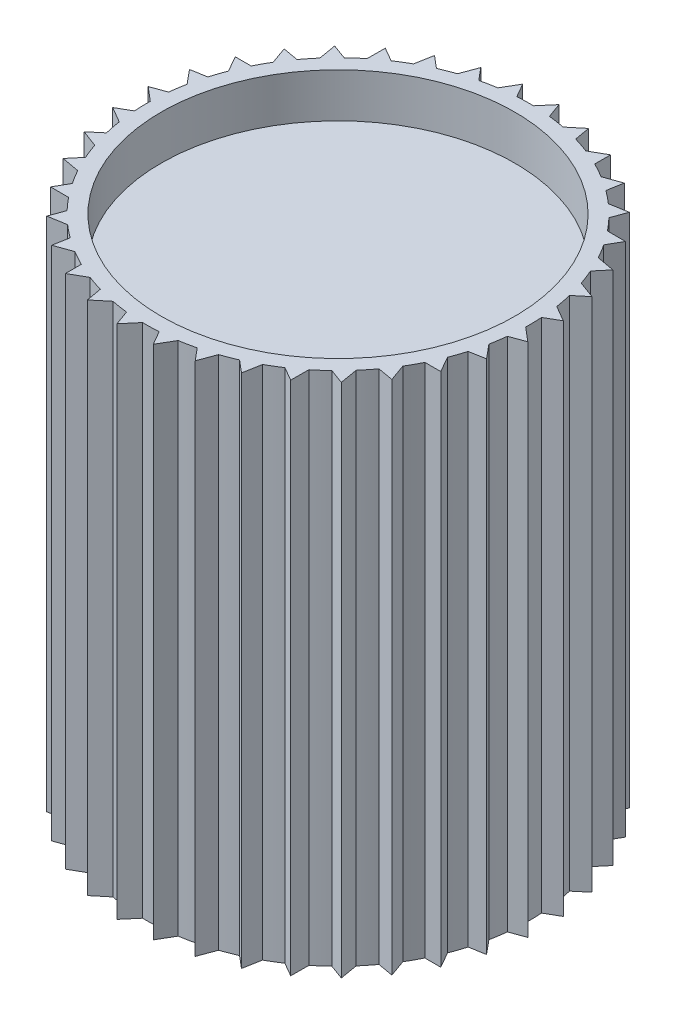
SolidWorks part; units mm, degrees
ref_plane "Front Plane" through (0, 0, 0) normal (0, 0, 1) x (1, 0, 0)
ref_plane "Top Plane" through (0, 0, 0) normal (0, 1, 0) x (1, 0, 0)
ref_plane "Right Plane" through (0, 0, 0) normal (1, 0, 0) x (0, 0, -1)
other "Configuration Table"
sketch "草图1" plane through (0, 0, 0) normal (0, 1, 0) x (1, 0, 0)
  circle A0 centre (0, 0) radius 13
  dimension "D1" = 26
extrude "凸台-拉伸1" add sketch "草图1" along normal blind 35
sketch "草图2" plane through (0, 35, 0) normal (0, 1, 0) x (1, 0, 0)
  circle A0 centre (0, 0) radius 12
  dimension "D1" = 24
extrude "切除-拉伸1" cut sketch "草图2" against normal blind 3
sketch "草图3" plane through (0, 35, 0) normal (0, 1, 0) x (1, 0, 0)
  line L0 (-12.1237, 4.6922) -> (-11.0446, 4.6922)
  line L1 (-12.1237, 4.6922) -> (-12.7329, 5.7609)
  line L2 (-11.0446, 4.6922) -> (-11.6538, 5.7609)
  line L3 (-12.7329, 5.7609) -> (-11.6538, 5.7609)
  line L4 (-11.1247, 6.7262) -> (-10.062, 6.5388)
  line L5 (-11.1247, 6.7262) -> (-11.5391, 7.8844)
  line L6 (-11.5391, 7.8844) -> (-10.4764, 7.6971)
  line L7 (-10.062, 6.5388) -> (-10.4764, 7.6971)
  line L8 (-9.7877, 8.5558) -> (-8.7737, 8.1867)
  line L9 (-9.7877, 8.5558) -> (-9.9947, 9.7684)
  line L10 (-9.9947, 9.7684) -> (-8.9807, 9.3993)
  line L11 (-8.7737, 8.1867) -> (-8.9807, 9.3993)
  line L12 (-8.1533, 10.1254) -> (-7.2188, 9.5859)
  line L13 (-8.1533, 10.1254) -> (-8.1465, 11.3556)
  line L14 (-8.1465, 11.3556) -> (-7.2121, 10.816)
  line L15 (-7.2188, 9.5859) -> (-7.2121, 10.816)
  line L16 (-6.2712, 11.3874) -> (-5.4446, 10.6938)
  line L17 (-6.2712, 11.3874) -> (-6.0509, 12.5977)
  line L18 (-6.0509, 12.5977) -> (-5.2243, 11.9041)
  line L19 (-5.4446, 10.6938) -> (-5.2243, 11.9041)
  line L20 (-4.1985, 12.3034) -> (-3.5049, 11.4767)
  line L21 (-4.1985, 12.3034) -> (-3.7714, 13.457)
  line L22 (-3.7714, 13.457) -> (-3.0778, 12.6304)
  line L23 (-3.5049, 11.4767) -> (-3.0778, 12.6304)
  line L24 (-1.9983, 12.8455) -> (-1.4587, 11.911)
  line L25 (-1.9983, 12.8455) -> (-1.3773, 13.9075)
  line L26 (-1.3773, 13.9075) -> (-0.8378, 12.973)
  line L27 (-1.4587, 11.911) -> (-0.8378, 12.973)
  line L28 (0.2627, 12.9973) -> (0.6317, 11.9834)
  line L29 (0.2627, 12.9973) -> (1.0586, 13.9354)
  line L30 (1.0586, 13.9354) -> (1.4277, 12.9214)
  line L31 (0.6317, 11.9834) -> (1.4277, 12.9214)
  line L32 (2.5157, 12.7543) -> (2.703, 11.6916)
  line L33 (2.5157, 12.7543) -> (3.4624, 13.5398)
  line L34 (3.4624, 13.5398) -> (3.6497, 12.4772)
  line L35 (2.703, 11.6916) -> (3.6497, 12.4772)
  line L36 (4.6922, 12.1237) -> (4.6922, 11.0446)
  line L37 (4.6922, 12.1237) -> (5.7609, 12.7329)
  line L38 (5.7609, 12.7329) -> (5.7609, 11.6538)
  line L39 (4.6922, 11.0446) -> (5.7609, 11.6538)
  line L40 (6.7262, 11.1247) -> (6.5388, 10.062)
  line L41 (6.7262, 11.1247) -> (7.8844, 11.5391)
  line L42 (7.8844, 11.5391) -> (7.6971, 10.4764)
  line L43 (6.5388, 10.062) -> (7.6971, 10.4764)
  line L44 (8.5558, 9.7877) -> (8.1867, 8.7737)
  line L45 (8.5558, 9.7877) -> (9.7684, 9.9947)
  line L46 (9.7684, 9.9947) -> (9.3993, 8.9807)
  line L47 (8.1867, 8.7737) -> (9.3993, 8.9807)
  line L48 (10.1254, 8.1533) -> (9.5859, 7.2188)
  line L49 (10.1254, 8.1533) -> (11.3556, 8.1465)
  line L50 (11.3556, 8.1465) -> (10.816, 7.2121)
  line L51 (9.5859, 7.2188) -> (10.816, 7.2121)
  line L52 (11.3874, 6.2712) -> (10.6938, 5.4446)
  line L53 (11.3874, 6.2712) -> (12.5977, 6.0509)
  line L54 (12.5977, 6.0509) -> (11.9041, 5.2243)
  line L55 (10.6938, 5.4446) -> (11.9041, 5.2243)
  line L56 (12.3034, 4.1985) -> (11.4767, 3.5049)
  line L57 (12.3034, 4.1985) -> (13.457, 3.7714)
  line L58 (13.457, 3.7714) -> (12.6304, 3.0778)
  line L59 (11.4767, 3.5049) -> (12.6304, 3.0778)
  line L60 (12.8455, 1.9983) -> (11.911, 1.4587)
  line L61 (12.8455, 1.9983) -> (13.9075, 1.3773)
  line L62 (13.9075, 1.3773) -> (12.973, 0.8378)
  line L63 (11.911, 1.4587) -> (12.973, 0.8378)
  line L64 (12.9973, -0.2627) -> (11.9834, -0.6317)
  line L65 (12.9973, -0.2627) -> (13.9354, -1.0586)
  line L66 (13.9354, -1.0586) -> (12.9214, -1.4277)
  line L67 (11.9834, -0.6317) -> (12.9214, -1.4277)
  line L68 (12.7543, -2.5157) -> (11.6916, -2.703)
  line L69 (12.7543, -2.5157) -> (13.5398, -3.4624)
  line L70 (13.5398, -3.4624) -> (12.4772, -3.6497)
  line L71 (11.6916, -2.703) -> (12.4772, -3.6497)
  line L72 (12.1237, -4.6922) -> (11.0446, -4.6922)
  line L73 (12.1237, -4.6922) -> (12.7329, -5.7609)
  line L74 (12.7329, -5.7609) -> (11.6538, -5.7609)
  line L75 (11.0446, -4.6922) -> (11.6538, -5.7609)
  line L76 (11.1247, -6.7262) -> (10.062, -6.5388)
  line L77 (11.1247, -6.7262) -> (11.5391, -7.8844)
  line L78 (11.5391, -7.8844) -> (10.4764, -7.6971)
  line L79 (10.062, -6.5388) -> (10.4764, -7.6971)
  line L80 (9.7877, -8.5558) -> (8.7737, -8.1867)
  line L81 (9.7877, -8.5558) -> (9.9947, -9.7684)
  line L82 (9.9947, -9.7684) -> (8.9807, -9.3993)
  line L83 (8.7737, -8.1867) -> (8.9807, -9.3993)
  line L84 (8.1533, -10.1254) -> (7.2188, -9.5859)
  line L85 (8.1533, -10.1254) -> (8.1465, -11.3556)
  line L86 (8.1465, -11.3556) -> (7.2121, -10.816)
  line L87 (7.2188, -9.5859) -> (7.2121, -10.816)
  line L88 (6.2712, -11.3874) -> (5.4446, -10.6938)
  line L89 (6.2712, -11.3874) -> (6.0509, -12.5977)
  line L90 (6.0509, -12.5977) -> (5.2243, -11.9041)
  line L91 (5.4446, -10.6938) -> (5.2243, -11.9041)
  line L92 (4.1985, -12.3034) -> (3.5049, -11.4767)
  line L93 (4.1985, -12.3034) -> (3.7714, -13.457)
  line L94 (3.7714, -13.457) -> (3.0778, -12.6304)
  line L95 (3.5049, -11.4767) -> (3.0778, -12.6304)
  line L96 (1.9983, -12.8455) -> (1.4587, -11.911)
  line L97 (1.9983, -12.8455) -> (1.3773, -13.9075)
  line L98 (1.3773, -13.9075) -> (0.8378, -12.973)
  line L99 (1.4587, -11.911) -> (0.8378, -12.973)
  line L100 (-0.2627, -12.9973) -> (-0.6317, -11.9834)
  line L101 (-0.2627, -12.9973) -> (-1.0586, -13.9354)
  line L102 (-1.0586, -13.9354) -> (-1.4277, -12.9214)
  line L103 (-0.6317, -11.9834) -> (-1.4277, -12.9214)
  line L104 (-2.5157, -12.7543) -> (-2.703, -11.6916)
  line L105 (-2.5157, -12.7543) -> (-3.4624, -13.5398)
  line L106 (-3.4624, -13.5398) -> (-3.6497, -12.4772)
  line L107 (-2.703, -11.6916) -> (-3.6497, -12.4772)
  line L108 (-4.6922, -12.1237) -> (-4.6922, -11.0446)
  line L109 (-4.6922, -12.1237) -> (-5.7609, -12.7329)
  line L110 (-5.7609, -12.7329) -> (-5.7609, -11.6538)
  line L111 (-4.6922, -11.0446) -> (-5.7609, -11.6538)
  line L112 (-6.7262, -11.1247) -> (-6.5388, -10.062)
  line L113 (-6.7262, -11.1247) -> (-7.8844, -11.5391)
  line L114 (-7.8844, -11.5391) -> (-7.6971, -10.4764)
  line L115 (-6.5388, -10.062) -> (-7.6971, -10.4764)
  line L116 (-8.5558, -9.7877) -> (-8.1867, -8.7737)
  line L117 (-8.5558, -9.7877) -> (-9.7684, -9.9947)
  line L118 (-9.7684, -9.9947) -> (-9.3993, -8.9807)
  line L119 (-8.1867, -8.7737) -> (-9.3993, -8.9807)
  line L120 (-10.1254, -8.1533) -> (-9.5859, -7.2188)
  line L121 (-10.1254, -8.1533) -> (-11.3556, -8.1465)
  line L122 (-11.3556, -8.1465) -> (-10.816, -7.2121)
  line L123 (-9.5859, -7.2188) -> (-10.816, -7.2121)
  line L124 (-11.3874, -6.2712) -> (-10.6938, -5.4446)
  line L125 (-11.3874, -6.2712) -> (-12.5977, -6.0509)
  line L126 (-12.5977, -6.0509) -> (-11.9041, -5.2243)
  line L127 (-10.6938, -5.4446) -> (-11.9041, -5.2243)
  line L128 (-12.3034, -4.1985) -> (-11.4767, -3.5049)
  line L129 (-12.3034, -4.1985) -> (-13.457, -3.7714)
  line L130 (-13.457, -3.7714) -> (-12.6304, -3.0778)
  line L131 (-11.4767, -3.5049) -> (-12.6304, -3.0778)
  line L132 (-12.8455, -1.9983) -> (-11.911, -1.4587)
  line L133 (-12.8455, -1.9983) -> (-13.9075, -1.3773)
  line L134 (-13.9075, -1.3773) -> (-12.973, -0.8378)
  line L135 (-11.911, -1.4587) -> (-12.973, -0.8378)
  line L136 (-12.9973, 0.2627) -> (-11.9834, 0.6317)
  line L137 (-12.9973, 0.2627) -> (-13.9354, 1.0586)
  line L138 (-13.9354, 1.0586) -> (-12.9214, 1.4277)
  line L139 (-11.9834, 0.6317) -> (-12.9214, 1.4277)
  line L140 (-12.7543, 2.5157) -> (-11.6916, 2.703)
  line L141 (-12.7543, 2.5157) -> (-13.5398, 3.4624)
  line L142 (-13.5398, 3.4624) -> (-12.4772, 3.6497)
  line L143 (-11.6916, 2.703) -> (-12.4772, 3.6497)
  line L144 (-11.6538, 5.7609) -> (-12.1237, 4.6922) construction
  circle A0 centre (0, 0) radius 13 construction
  circle A1 centre (0, 0) radius 12 construction
  point P151 (0, 0)
  dimension "D1" = 36
extrude "凸台-拉伸2" add sketch "草图3" against normal through all
